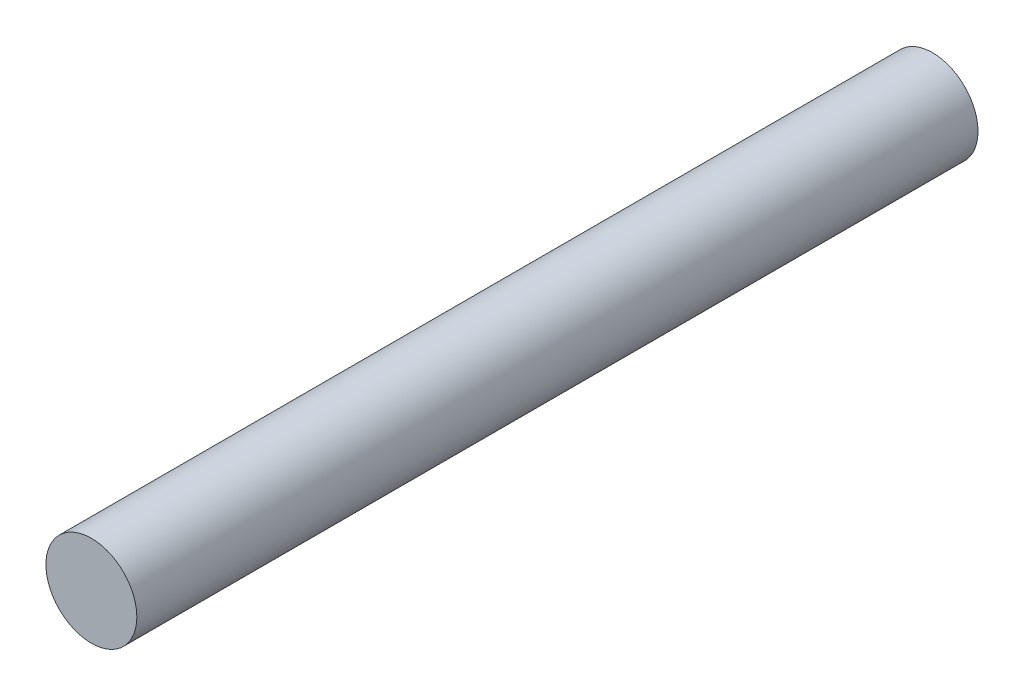
SolidWorks part; units mm, degrees
ref_plane "Piano frontale" through (0, 0, 0) normal (0, 0, 1) x (1, 0, 0)
ref_plane "Piano superiore" through (0, 0, 0) normal (0, 1, 0) x (1, 0, 0)
ref_plane "Piano destro" through (0, 0, 0) normal (1, 0, 0) x (0, 0, -1)
sketch "Schizzo1" plane through (0, 0, 0) normal (0, 0, 1) x (1, 0, 0)
  circle A0 centre (0, 0) radius 2
  dimension "D1" = 4
extrude "Estrusione-Estrusione1" add sketch "Schizzo1" along normal blind 37
